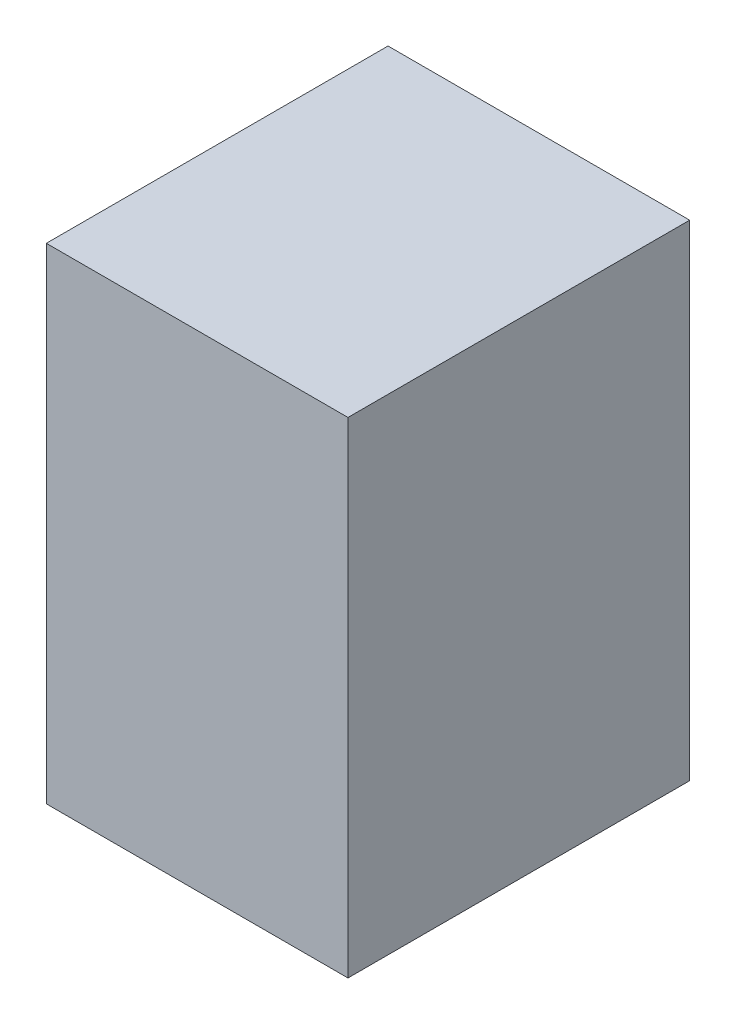
SolidWorks part; units mm, degrees
ref_plane "Front Plane" through (0, 0, 0) normal (0, 0, 1) x (1, 0, 0)
ref_plane "Top Plane" through (0, 0, 0) normal (0, 1, 0) x (1, 0, 0)
ref_plane "Right Plane" through (0, 0, 0) normal (1, 0, 0) x (0, 0, -1)
sketch "Sketch1" plane through (0, 0, 0) normal (0, 1, 0) x (1, 0, 0)
  line L1 (-32, -36.25) -> (32, -36.25)
  line L2 (-32, -36.25) -> (-32, 36.25)
  line L3 (-32, 36.25) -> (32, 36.25)
  line L4 (32, -36.25) -> (32, 36.25)
  line L5 (-32, -36.25) -> (32, 36.25) construction
  line L6 (-32, 36.25) -> (32, -36.25) construction
  point P0 (0, 0)
  dimension "D1" = 64
  dimension "D2" = 72.5
extrude "Boss-Extrude1" add sketch "Sketch1" along normal blind 103
